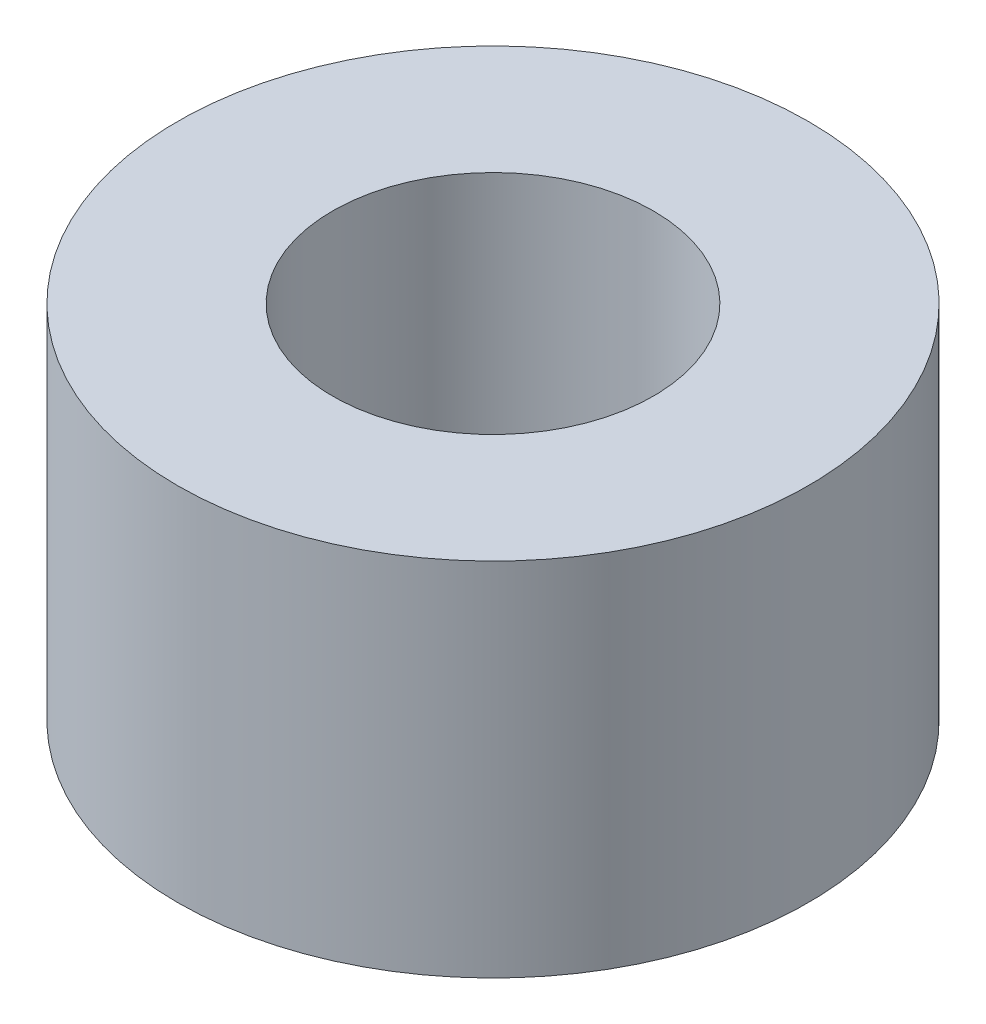
SolidWorks part; units mm, degrees
ref_plane "Plan de face" through (0, 0, 0) normal (0, 0, 1) x (1, 0, 0)
ref_plane "Plan de dessus" through (0, 0, 0) normal (0, 1, 0) x (1, 0, 0)
ref_plane "Plan de droite" through (0, 0, 0) normal (1, 0, 0) x (0, 0, -1)
sketch "Esquisse1" plane through (0, 0, 0) normal (0, 1, 0) x (1, 0, 0)
  circle A0 centre (0, 0) radius 6.242
  circle A1 centre (0, 0) radius 3.175
  dimension "D1" = 12.4841
  dimension "D2" = 6.35
extrude "Boss.-Extru.1" add sketch "Esquisse1" along normal blind 7.145
